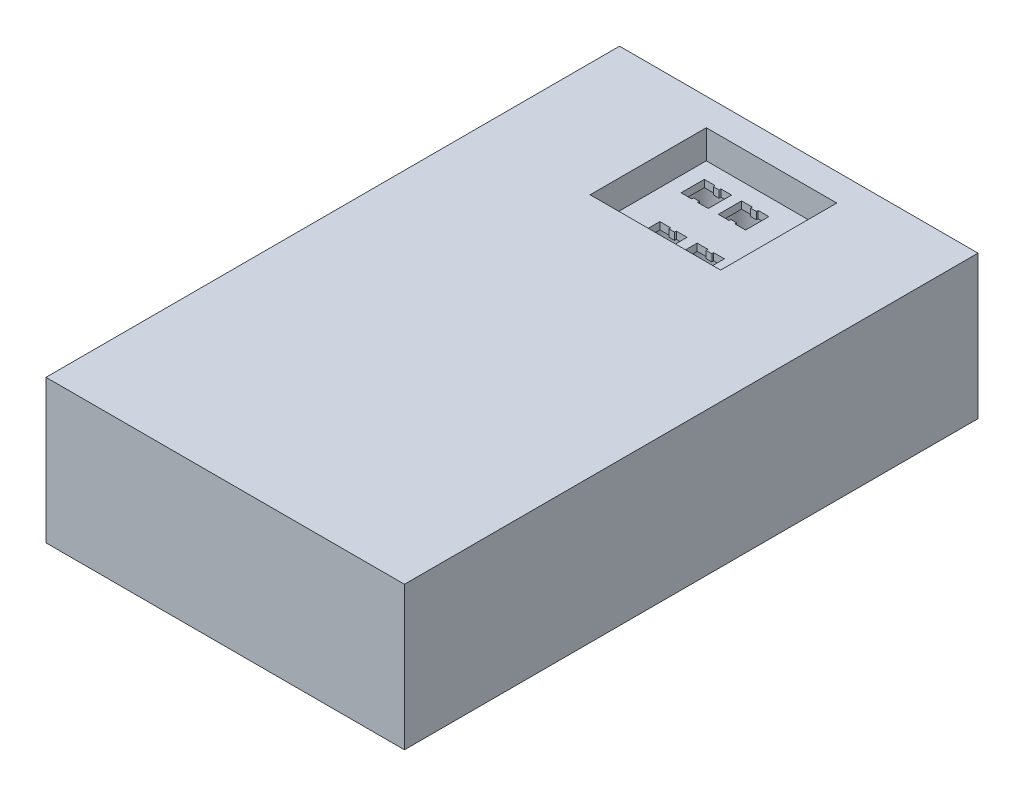
SolidWorks part; units mm, degrees
ref_plane "Front Plane" through (0, 0, 0) normal (0, 0, 1) x (1, 0, 0)
ref_plane "Top Plane" through (0, 0, 0) normal (0, 1, 0) x (1, 0, 0)
ref_plane "Right Plane" through (0, 0, 0) normal (1, 0, 0) x (0, 0, -1)
sketch "Sketch1" plane through (0, 0, 0) normal (0, 0, 1) x (1, 0, 0)
  line L1 (25, -10) -> (-25, -10)
  line L2 (25, -10) -> (25, 10)
  line L3 (25, 10) -> (-25, 10)
  line L4 (-25, -10) -> (-25, 10)
  line L5 (25, -10) -> (-25, 10) construction
  line L6 (25, 10) -> (-25, -10) construction
  point P0 (0, 0)
  dimension "D1" = 20
  dimension "D2" = 50
extrude "Boss-Extrude1" add sketch "Sketch1" along normal mid plane 80
sketch "Sketch2" plane through (0, 10, 0) normal (0, 1, 0) x (1, 0, 0)
  line L0 (0, -42.6274) -> (0, 41.738) construction
  line L1 (25, 40) -> (-25, 40) construction
  line L2 (9.1, 20) -> (-9.1, 20)
  line L3 (9.1, 20) -> (9.1, 36.2)
  line L4 (9.1, 36.2) -> (-9.1, 36.2)
  line L5 (-9.1, 20) -> (-9.1, 36.2)
  line L6 (9.1, 20) -> (-9.1, 36.2) construction
  line L7 (9.1, 36.2) -> (-9.1, 20) construction
  point P3 (0, 28.1)
  dimension "D1" = 16.2
  dimension "D2" = 18.2
  dimension "D3" = 3.8
extrude "Cut-Extrude1" cut sketch "Sketch2" against normal blind 4
sketch "Sketch3" plane through (0, 6, 0) normal (0, 1, 0) x (1, 0, 0)
  line L0 (9.1, 36.2) -> (-9.1, 36.2) construction
  line L1 (-9.1, 20) -> (9.1, 20) construction
  line L2 (-9.1, 36.2) -> (-9.1, 20) construction
  circle A0 centre (-5.1, 32.2) radius 2.5
  circle A1 centre (0.1, 32.2) radius 2.5
  circle A2 centre (-3.1, 24) radius 2.5
  circle A3 centre (2.1, 24) radius 2.5
  point P14 (0, 0)
  point P15 (0, 0)
  dimension "D1" = 5
  dimension "D2" = 5
  dimension "D3" = 5
  dimension "D4" = 5
  dimension "D5" = 5.2
  dimension "D6" = 5.2
  dimension "D7" = 4
  dimension "D8" = 4
  dimension "D9" = 6
  dimension "D10" = 4
extrude "Cut-Extrude2" cut sketch "Sketch3" along normal blind 15 from surface at -16 starting at face at (0, -10, 0)
sketch "Sketch4" plane through (0, 6, 0) normal (0, 1, 0) x (1, 0, 0)
  line L0 (-5.5, 33.8248) -> (-7, 33.8248)
  line L1 (-3.2, 30.5752) -> (-4.7, 30.5752)
  line L2 (-3.2, 30.5752) -> (-3.2, 33.8248)
  line L3 (-3.2, 33.8248) -> (-4.7, 33.8248)
  line L4 (-7, 30.5752) -> (-7, 33.8248)
  line L5 (-3.2, 30.5752) -> (-7, 33.8248) construction
  line L6 (-3.2, 33.8248) -> (-7, 30.5752) construction
  line L7 (-4.7, 33.5716) -> (-5.5, 33.5716)
  line L8 (-4.7, 33.5716) -> (-4.7, 33.8248)
  line L9 (-5.5, 30.5752) -> (-7, 30.5752)
  line L10 (-5.5, 33.5716) -> (-5.5, 33.8248)
  line L11 (-5.1, 33.8264) -> (-5.1075, 33.8311) construction
  line L12 (-2.5, 29.0068) -> (-2.5, 35.421) construction
  line L13 (-5.1, 30.5784) -> (-5.1, 33.5716) construction
  line L14 (-4.7, 30.5752) -> (-4.7, 30.8284)
  line L15 (-4.7, 30.8284) -> (-5.5, 30.8284)
  line L16 (-5.5, 30.5752) -> (-5.5, 30.8284)
  line L17 (-5.1, 33.8264) -> (-5.1, 35.1905) construction
  line L18 (0.1, 30.5784) -> (0.1, 33.5716) construction
  line L19 (0.1, 33.8264) -> (0.1075, 33.8311) construction
  line L20 (-1.8, 33.8248) -> (2, 30.5752) construction
  line L21 (-1.8, 30.5752) -> (2, 33.8248) construction
  line L22 (0.5, 30.5752) -> (0.5, 30.8284)
  line L23 (-0.3, 30.8284) -> (0.5, 30.8284)
  line L24 (-0.3, 30.5752) -> (-0.3, 30.8284)
  line L25 (0.5, 33.5716) -> (0.5, 33.8248)
  line L26 (0.5, 30.5752) -> (2, 30.5752)
  line L27 (-0.3, 33.5716) -> (-0.3, 33.8248)
  line L28 (-0.3, 33.5716) -> (0.5, 33.5716)
  line L29 (2, 30.5752) -> (2, 33.8248)
  line L30 (-1.8, 33.8248) -> (-0.3, 33.8248)
  line L31 (-1.8, 30.5752) -> (-1.8, 33.8248)
  line L32 (-1.8, 30.5752) -> (-0.3, 30.5752)
  line L33 (0.5, 33.8248) -> (2, 33.8248)
  line L34 (2.1, 26.5) -> (2.1, 20.9074) construction
  line L35 (4.6, 24) -> (-0.5, 24) construction
  line L36 (-0.5, 26.5) -> (-0.5, 20.6206) construction
  line L37 (0.2, 25.6248) -> (4, 22.3752) construction
  line L38 (0.2, 22.3752) -> (4, 25.6248) construction
  line L39 (-3.1, 25.5677) -> (-3.1, 22.7262) construction
  line L40 (2.1, 25.5677) -> (2.1, 22.7262) construction
  line L41 (2.5, 22.3752) -> (4, 22.3752)
  line L42 (0.2, 25.6248) -> (1.7, 25.6247)
  line L43 (0.2, 25.6248) -> (0.2, 22.3752)
  line L44 (0.2, 22.3752) -> (1.7, 22.3751)
  line L45 (4, 25.6248) -> (4, 22.3752)
  line L46 (1.7, 22.6283) -> (2.5, 22.6284)
  line L47 (1.7, 22.6283) -> (1.7, 22.3751)
  line L48 (2.5, 25.6247) -> (4, 25.6248)
  line L49 (2.5, 22.6284) -> (2.5, 22.3752)
  line L50 (1.7, 25.6247) -> (1.7, 25.3715)
  line L51 (1.7, 25.3715) -> (2.5, 25.3715)
  line L52 (2.5, 25.6247) -> (2.5, 25.3715)
  line L53 (-1.2, 22.3752) -> (-5, 25.6248) construction
  line L54 (-1.2, 25.6248) -> (-5, 22.3752) construction
  line L55 (-3.5, 25.6247) -> (-3.5, 25.3715)
  line L56 (-2.7, 25.3715) -> (-3.5, 25.3715)
  line L57 (-2.7, 25.6247) -> (-2.7, 25.3715)
  line L58 (-3.5, 22.6284) -> (-3.5, 22.3752)
  line L59 (-3.5, 25.6247) -> (-5, 25.6248)
  line L60 (-2.7, 22.6283) -> (-2.7, 22.3751)
  line L61 (-2.7, 22.6283) -> (-3.5, 22.6284)
  line L62 (-5, 25.6248) -> (-5, 22.3752)
  line L63 (-1.2, 22.3752) -> (-2.7, 22.3751)
  line L64 (-1.2, 25.6248) -> (-1.2, 22.3752)
  line L65 (-1.2, 25.6248) -> (-2.7, 25.6247)
  line L66 (-3.5, 22.3752) -> (-5, 22.3752)
  circle A0 centre (-5.1, 32.2) radius 2.5 construction
  circle A1 centre (2.1, 24) radius 2.5 construction
  point P0 (-5.1, 32.2)
  point P6 (-5.1, 30.5784)
  point P11 (-5.1, 33.8264)
  point P41 (0.1, 32.2)
  point P62 (2.1, 24)
  point P80 (-3.1, 24)
  point P81 (4, 22.3751)
  point P82 (4, 22.3752)
  dimension "D1" = 0.4
  dimension "D2" = 0.4
  dimension "D3" = 3.8
  dimension "D4" = 0.8
  dimension "D5" = 0.2532
  dimension "D6" = 0.2532
  dimension "D7" = 0.4
  dimension "D8" = 2.6
  dimension "D9" = 0.2532
  dimension "D10" = 0.8
  dimension "D11" = 0.4
  dimension "D12" = 0.4
  dimension "D13" = 0.4
  dimension "D14" = 0.4
  dimension "D15" = 0.2532
  dimension "D16" = 3.8
  dimension "D17" = 1.5
  dimension "D18" = 1.5
  dimension "D20" = 2.6
extrude "Cut-Extrude3" cut sketch "Sketch4" against normal blind 1
sketch "Sketch6" plane through (0, -10, 0) normal (0, -1, 0) x (1, 0, 0)
  line L0 (-25, -40) -> (25, -40) construction
  line L1 (22.5, -36.2) -> (4, -36.2)
  line L2 (22.5, -36.2) -> (22.5, 39)
  line L3 (22.5, 39) -> (-22.5, 39)
  line L4 (-22.5, -36.2) -> (-22.5, 39)
  line L5 (-25, 40) -> (25, 40) construction
  line L6 (-18.8326, -36.2) -> (12.2453, -36.2) construction
  line L7 (-9.1, -36.2) -> (-22.5, -36.2)
  line L8 (-9.1, -36.2) -> (-5.1, -36.2)
  line L9 (-5.1, -29.2) -> (-5.1, -36.2)
  line L10 (9.1, -36.2) -> (-9.1, -36.2) construction
  line L11 (-5.1, -36.2) -> (-5.1, -26.8821) construction
  line L12 (-5.1, -29.2) -> (-3.1, -29.2)
  line L13 (-3.1, -29.9517) -> (-3.1, -18.152) construction
  line L14 (-2.7, -25.3715) -> (-3.5, -25.3715) construction
  line L15 (2.1, -19.0646) -> (2.1, -30.2333) construction
  line L16 (-9.1, -20) -> (9.1, -20) construction
  line L17 (-3.1, -20) -> (2.1, -20)
  line L18 (2.1, -20) -> (2.1, -29.2)
  line L19 (2.1, -29.2) -> (0, -29.2)
  line L20 (0, -29.2) -> (0, -36.2)
  line L21 (0, -36.2) -> (4, -36.2)
  line L24 (-3.1, -20) -> (-3.1, -29.2)
  point P0 (0, 0)
  point P30 (-3.1, -20)
  point P39 (2.1, -20)
  point P40 (2.1, -30.2333)
  point P41 (-3.7012, -29.9517)
  point P45 (-3.1, -25.3715)
  point P46 (-3.1, -18.152)
  point P47 (-1.9327, -20)
  point P48 (2.1, -19.0646)
  point P49 (2.7008, -29.2)
  point P50 (1.5248, -29.2)
  point P51 (0, 0)
  dimension "D1" = 3.8
  dimension "D2" = 45
  dimension "D3" = 1
  dimension "D4" = 22.5
  dimension "D5" = 7
  dimension "D6" = 4
  dimension "D7" = 4
  dimension "D8" = 17.4
  dimension "D9" = 5.2
extrude "Cut-Extrude4" cut sketch "Sketch6" against normal blind 12
sketch "Sketch7" plane through (0, -10, 0) normal (0, -1, 0) x (1, 0, 0)
  line L1 (-9.1, -20) -> (9.1, -20)
  line L2 (-9.1, -20) -> (-9.1, -36.2)
  line L3 (-9.1, -36.2) -> (9.1, -36.2)
  line L4 (9.1, -20) -> (9.1, -36.2)
extrude "Boss-Extrude3" add sketch "Sketch7" against normal blind 1.5
sketch "Sketch8" plane through (0, -10, 0) normal (0, -1, 0) x (1, 0, 0)
  line L0 (-3.1, -20) -> (-3.1, -27.4718) construction
  line L1 (-3.1, -26.5) -> (-3.1, -29.2) construction
  line L2 (2.1, -20) -> (2.1, -27.85) construction
  line L3 (2.1, -29.2) -> (2.1, -26.5) construction
  line L4 (-5, -24) -> (4.3226, -24) construction
  line L5 (-5, -25.6248) -> (-5, -22.3752) construction
  line L6 (-5.1, -30.8284) -> (-5.1, -34.3621) construction
  line L7 (-5.5, -30.8284) -> (-4.7, -30.8284) construction
  line L8 (0.1, -30.8284) -> (0.1, -34.3621) construction
  line L9 (-0.3, -30.8284) -> (0.5, -30.8284) construction
  line L10 (-7, -32.2) -> (2.2852, -32.2) construction
  line L11 (-7, -33.8248) -> (-7, -30.5752) construction
  circle A0 centre (-3.1, -24) radius 1
  circle A1 centre (2.1, -24) radius 1
  circle A2 centre (-5.1, -32.2) radius 1
  circle A3 centre (0.1, -32.2) radius 1
  point P34 (0, 0)
  point P35 (0, 0)
  point P36 (0, 0)
  dimension "D1" = 2
  dimension "D2" = 2
  dimension "D3" = 2
  dimension "D4" = 2
extrude "Cut-Extrude5" cut sketch "Sketch8" against normal up to next
